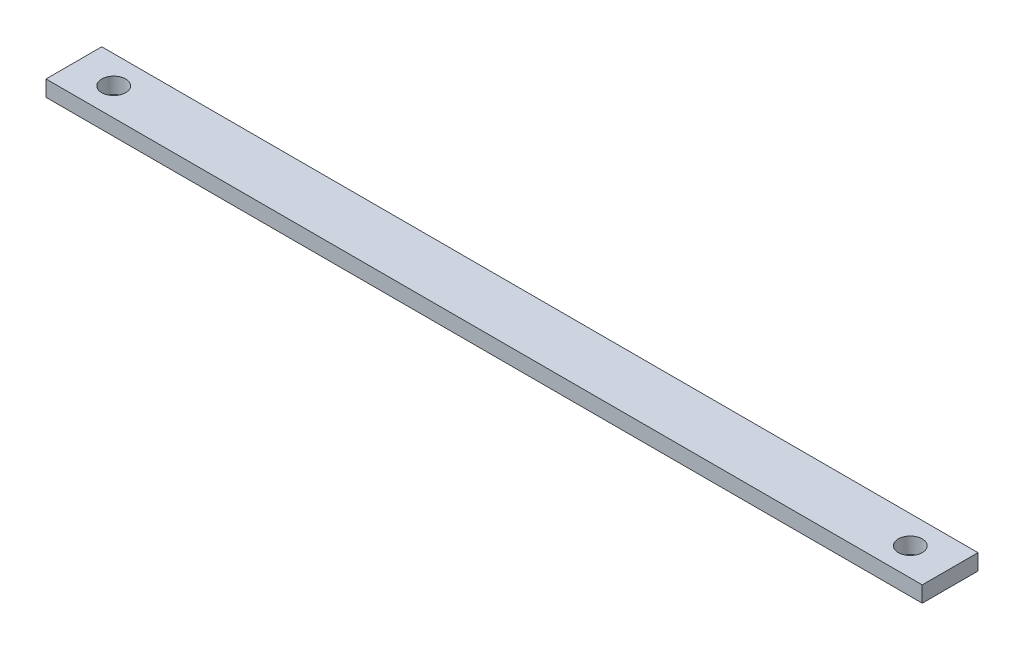
SolidWorks part; units mm, degrees
ref_plane "Front Plane" through (0, 0, 0) normal (0, 0, 1) x (1, 0, 0)
ref_plane "Top Plane" through (0, 0, 0) normal (0, 1, 0) x (1, 0, 0)
ref_plane "Right Plane" through (0, 0, 0) normal (1, 0, 0) x (0, 0, -1)
sketch "Sketch3" plane through (0, 0, 0) normal (0, 1, 0) x (1, 0, 0)
  line L0 (-55, 0) -> (55, 0) construction
  line L1 (-55, -3.5) -> (55, -3.5)
  line L2 (-55, -3.5) -> (-55, 3.5)
  line L3 (-55, 3.5) -> (55, 3.5)
  line L4 (55, -3.5) -> (55, 3.5)
  line L5 (-55, -3.5) -> (55, 3.5) construction
  line L6 (-55, 3.5) -> (55, -3.5) construction
  line L7 (0, 0) -> (0, 16.9167) construction
  circle A0 centre (-50, 0) radius 1.5
  circle A1 centre (50, 0) radius 1.5
  point P0 (0, 0)
  dimension "D4" = 3
  dimension "D1" = 7
  dimension "D2" = 110
  dimension "D3" = 5
extrude "Boss-Extrude1" add sketch "Sketch3" along normal blind 2
